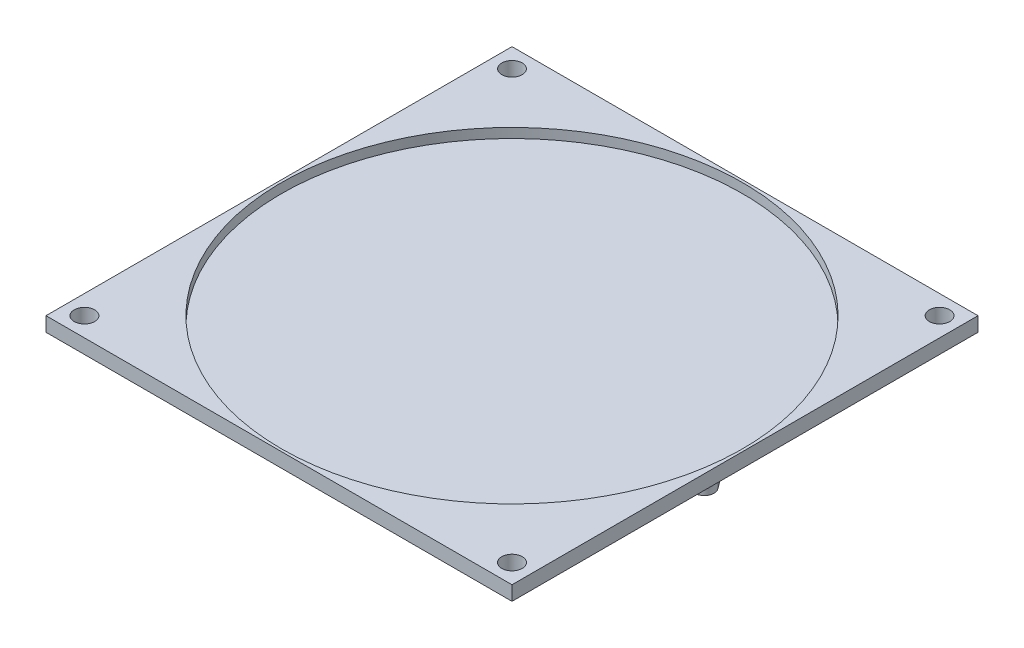
SolidWorks part; units mm, degrees
ref_plane "Front Plane" through (0, 0, 0) normal (0, 0, 1) x (1, 0, 0)
ref_plane "Top Plane" through (0, 0, 0) normal (0, 1, 0) x (1, 0, 0)
ref_plane "Right Plane" through (0, 0, 0) normal (1, 0, 0) x (0, 0, -1)
sketch "Sketch2" plane through (0, 0, 0) normal (0, 1, 0) x (1, 0, 0)
  line L1 (0, 0) -> (154.0002, 0)
  line L2 (0, 0) -> (0, 154.0002)
  line L3 (0, 154.0002) -> (154.0002, 154.0002)
  line L4 (154.0002, 0) -> (154.0002, 154.0002)
  dimension "D1" = 154.0002
  dimension "D2" = 154.0002
extrude "Boss-Extrude1" add sketch "Sketch2" along normal blind 4.7625
sketch "Sketch4" plane through (0, 4.7625, 0) normal (0, 1, 0) x (1, 0, 0)
  line L0 (0, 154.0002) -> (154.0002, 0) construction
  line L1 (0, 0) -> (154.0002, 154.0002) construction
  circle A0 centre (77.0001, 77.0001) radius 76.2
  dimension "D1" = 152.4
extrude "Cut-Extrude1" cut sketch "Sketch4" against normal blind 3.175
sketch "Sketch5" plane through (0, 4.7625, 0) normal (0, 1, 0) x (1, 0, 0)
  line L0 (6.35, 154.0002) -> (6.35, 147.6502) construction
  line L1 (154.0002, 154.0002) -> (0, 154.0002) construction
  line L3 (147.6502, 147.6502) -> (154.0002, 147.6502) construction
  line L4 (0, 154.0002) -> (0, 0) construction
  line L5 (154.0002, 0) -> (154.0002, 154.0002) construction
  line L6 (147.6502, 154.0002) -> (147.6502, 147.6502) construction
  line L7 (0, 147.6502) -> (6.35, 147.6502) construction
  line L8 (0, 6.35) -> (6.35, 6.35) construction
  line L9 (6.35, 6.35) -> (6.35, 0) construction
  line L10 (0, 0) -> (154.0002, 0) construction
  line L11 (147.6502, 0) -> (147.6502, 6.35) construction
  line L12 (147.6502, 6.35) -> (154.0002, 6.35) construction
  circle A0 centre (6.35, 6.35) radius 3.3782
  circle A1 centre (6.35, 147.6502) radius 3.3782
  circle A2 centre (147.6502, 147.6502) radius 3.3782
  circle A3 centre (147.6502, 6.35) radius 3.3782
  dimension "D8" = 6.7564
  dimension "D9" = 6.7564
  dimension "D10" = 6.7564
  dimension "D11" = 6.7564
  dimension "D1" = 6.35
  dimension "D2" = 6.35
  dimension "D3" = 6.35
  dimension "D4" = 6.35
  dimension "D5" = 6.35
  dimension "D6" = 6.35
  dimension "D7" = 6.35
extrude "Cut-Extrude2" cut sketch "Sketch5" against normal through all
sketch "Sketch7" plane through (0, 0, 0) normal (0, -1, 0) x (1, 0, 0)
  line L2 (96.0521, -88.4109) -> (110.1169, -69.3609)
  line L3 (109.2842, -89.7001) -> (123.349, -89.7001)
  line L4 (126.524, -86.5251) -> (126.524, -67.4751)
  line L5 (120.7947, -65.5893) -> (106.7299, -84.6393)
  line L6 (109.2842, -89.7001) -> (123.349, -89.7001)
  line L7 (126.524, -86.5251) -> (126.524, -67.4751)
  line L8 (120.7947, -65.5893) -> (106.7299, -84.6393)
  line L9 (150.1137, -64.3001) -> (136.049, -64.3001)
  line L10 (132.874, -67.4751) -> (132.874, -86.5251)
  line L11 (138.6032, -88.4109) -> (152.668, -69.3609)
  line L12 (150.1137, -64.3001) -> (136.049, -64.3001)
  line L13 (132.874, -67.4751) -> (132.874, -86.5251)
  line L14 (138.6032, -88.4109) -> (152.668, -69.3609)
  line L15 (107.5626, -64.3001) -> (93.4979, -64.3001)
  line L16 (96.0521, -88.4109) -> (110.1169, -69.3609)
  line L17 (107.5626, -64.3001) -> (93.4979, -64.3001)
  line L18 (58.2758, -65.2116) -> (38.9091, -84.2616)
  line L19 (25.2516, -88.7886) -> (44.6183, -69.7386)
  line L20 (42.3918, -64.3001) -> (23.0251, -64.3001)
  line L21 (19.8501, -67.4751) -> (19.8501, -86.5251)
  line L22 (25.2516, -88.7886) -> (44.6183, -69.7386)
  line L23 (42.3918, -64.3001) -> (23.0251, -64.3001)
  line L24 (19.8501, -67.4751) -> (19.8501, -86.5251)
  line L25 (41.1355, -89.7001) -> (60.5023, -89.7001)
  line L26 (58.2758, -65.2116) -> (38.9091, -84.2616)
  line L27 (41.1355, -89.7001) -> (60.5023, -89.7001)
  arc A4 (106.7299, -84.6393) -> (109.2842, -89.7001) centre (109.2842, -86.5251) ccw
  arc A5 (123.349, -89.7001) -> (126.524, -86.5251) centre (123.349, -86.5251) ccw
  arc A6 (126.524, -67.4751) -> (120.7947, -65.5893) centre (123.349, -67.4751) ccw
  arc A7 (106.7299, -84.6393) -> (109.2842, -89.7001) centre (109.2842, -86.5251) ccw
  arc A8 (123.349, -89.7001) -> (126.524, -86.5251) centre (123.349, -86.5251) ccw
  arc A9 (126.524, -67.4751) -> (120.7947, -65.5893) centre (123.349, -67.4751) ccw
  arc A11 (152.668, -69.3609) -> (150.1137, -64.3001) centre (150.1137, -67.4751) ccw
  arc A12 (136.049, -64.3001) -> (132.874, -67.4751) centre (136.049, -67.4751) ccw
  arc A13 (132.874, -86.5251) -> (138.6032, -88.4109) centre (136.049, -86.5251) ccw
  arc A14 (152.668, -69.3609) -> (150.1137, -64.3001) centre (150.1137, -67.4751) ccw
  arc A15 (136.049, -64.3001) -> (132.874, -67.4751) centre (136.049, -67.4751) ccw
  arc A16 (132.874, -86.5251) -> (138.6032, -88.4109) centre (136.049, -86.5251) ccw
  arc A19 (93.4979, -64.3001) -> (90.7482, -69.0626) centre (93.4979, -67.4751) ccw
  arc A20 (90.7482, -84.9376) -> (90.7482, -69.0626) centre (77.0001, -77.0001) ccw
  arc A21 (90.7482, -84.9376) -> (96.0521, -88.4109) centre (93.4979, -86.5251) ccw
  arc A22 (110.1169, -69.3609) -> (107.5626, -64.3001) centre (107.5626, -67.4751) ccw
  arc A23 (93.4979, -64.3001) -> (90.7482, -69.0626) centre (93.4979, -67.4751) ccw
  arc A24 (90.7482, -84.9376) -> (90.7482, -69.0626) centre (77.0001, -77.0001) ccw
  arc A25 (90.7482, -84.9376) -> (96.0521, -88.4109) centre (93.4979, -86.5251) ccw
  arc A26 (110.1169, -69.3609) -> (107.5626, -64.3001) centre (107.5626, -67.4751) ccw
  arc A27 (19.8501, -86.5251) -> (25.2516, -88.7886) centre (23.0251, -86.5251) ccw
  arc A28 (44.6183, -69.7386) -> (42.3918, -64.3001) centre (42.3918, -67.4751) ccw
  arc A29 (23.0251, -64.3001) -> (19.8501, -67.4751) centre (23.0251, -67.4751) ccw
  arc A30 (19.8501, -86.5251) -> (25.2516, -88.7886) centre (23.0251, -86.5251) ccw
  arc A31 (44.6183, -69.7386) -> (42.3918, -64.3001) centre (42.3918, -67.4751) ccw
  arc A32 (23.0251, -64.3001) -> (19.8501, -67.4751) centre (23.0251, -67.4751) ccw
  arc A35 (60.5023, -89.7001) -> (63.2519, -84.9376) centre (60.5023, -86.5251) ccw
  arc A36 (63.2519, -69.0626) -> (63.2519, -84.9376) centre (77.0001, -77.0001) ccw
  arc A37 (63.2519, -69.0626) -> (58.2758, -65.2116) centre (60.5023, -67.4751) ccw
  arc A38 (38.9091, -84.2616) -> (41.1355, -89.7001) centre (41.1355, -86.5251) ccw
  arc A39 (60.5023, -89.7001) -> (63.2519, -84.9376) centre (60.5023, -86.5251) ccw
  arc A40 (63.2519, -69.0626) -> (63.2519, -84.9376) centre (77.0001, -77.0001) ccw
  arc A41 (63.2519, -69.0626) -> (58.2758, -65.2116) centre (60.5023, -67.4751) ccw
  arc A42 (38.9091, -84.2616) -> (41.1355, -89.7001) centre (41.1355, -86.5251) ccw
  dimension "D1" = 0
  dimension "D2" = 0
  dimension "D3" = 0
  dimension "D4" = 0
  dimension "D5" = 0
extrude "Boss-Extrude2" add sketch "Sketch7" along normal up to surface (3.175 mm away)
